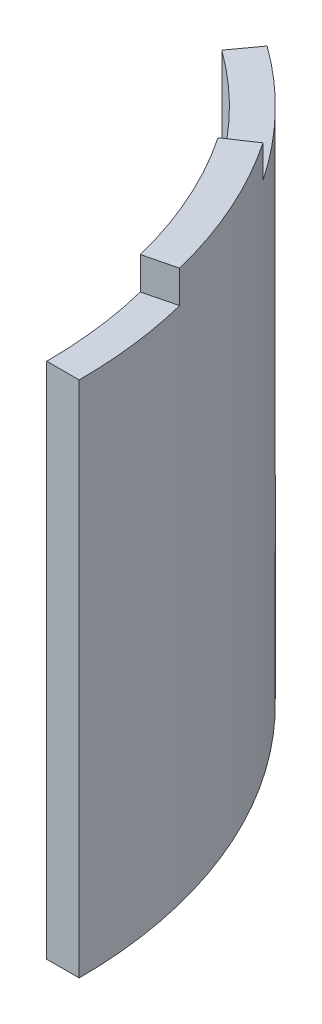
SolidWorks part; units mm, degrees
ref_plane "Front Plane" through (0, 0, 0) normal (0, 0, 1) x (1, 0, 0)
ref_plane "Top Plane" through (0, 0, 0) normal (0, 1, 0) x (1, 0, 0)
ref_plane "Right Plane" through (0, 0, 0) normal (1, 0, 0) x (0, 0, -1)
sketch "Sketch1" plane through (0, 0, 0) normal (0, 1, 0) x (1, 0, 0)
  line L0 (25.3806, 34.9334) -> (27.2468, 37.502)
  line L1 (43.18, 0) -> (46.355, 0)
  arc A0 (43.18, 0) -> (25.3806, 34.9334) centre (0, 0) ccw
  arc A1 (46.355, 0) -> (27.2468, 37.502) centre (0, 0) ccw
  dimension "D1" = 3.175
  dimension "D2" = 43.18
  dimension "D3" = 54
extrude "Boss-Extrude1" add sketch "Sketch1" along normal mid plane 50.7
sketch "Sketch2" plane through (0, 25.35, 0) normal (0, 1, 0) x (1, 0, 0)
  line L0 (35.7978, 24.1459) -> (38.43, 25.9214)
  line L1 (41.8974, 10.4462) -> (44.9781, 11.2143)
  line L2 (27.2468, 37.502) -> (25.3806, 34.9334) construction
  arc A0 (38.43, 25.9214) -> (44.9781, 11.2143) centre (0, 0) cw
  arc A1 (46.355, 0) -> (27.2468, 37.502) centre (0, 0) ccw construction
  arc A2 (41.8974, 10.4462) -> (35.7978, 24.1459) centre (0, 0) ccw
  arc A3 (43.18, 0) -> (25.3806, 34.9334) centre (0, 0) ccw construction
  point P7 (0, 0)
  dimension "D1" = 20
  dimension "D2" = 20
extrude "Boss-Extrude2" add sketch "Sketch2" along normal blind 3.175
